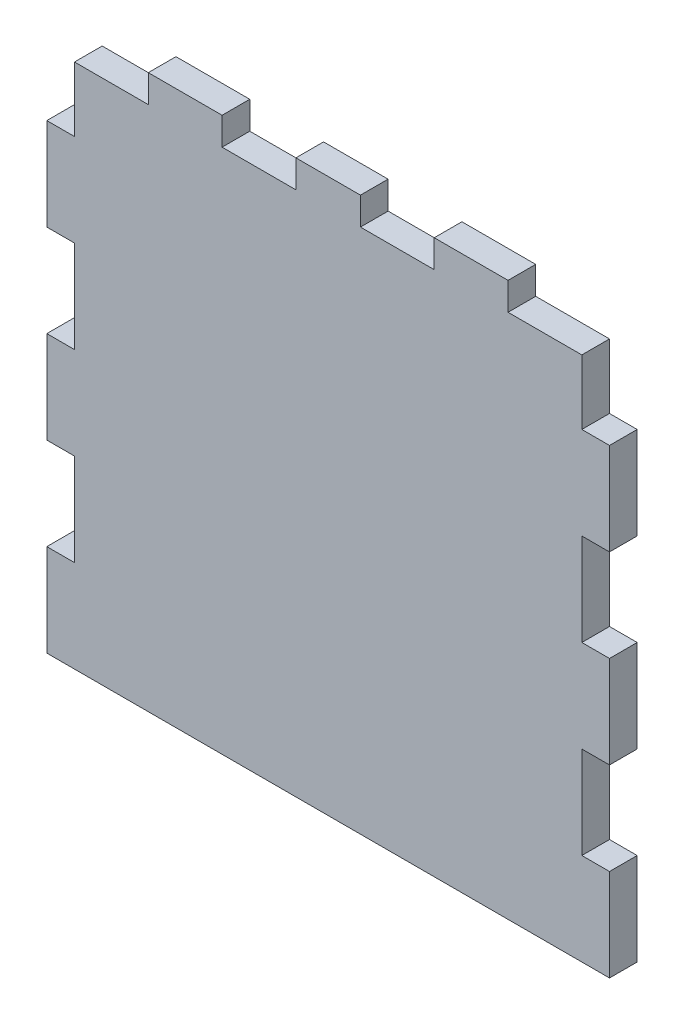
SolidWorks part; units mm, degrees
material "Beech"
ref_plane "Front Plane" through (0, 0, 0) normal (0, 0, 1) x (1, 0, 0)
ref_plane "Top Plane" through (0, 0, 0) normal (0, 1, 0) x (1, 0, 0)
ref_plane "Right Plane" through (0, 0, 0) normal (1, 0, 0) x (0, 0, -1)
sketch "Sketch1" plane through (0, 0, 0) normal (0, 0, 1) x (1, 0, 0)
  line L0 (27.5, -3) -> (-27.5, -3)
  line L1 (-27.5, -3) -> (-27.5, -60)
  line L2 (-27.5, -57) -> (27.5, -57)
  line L3 (27.5, -60) -> (27.5, -3)
  line L8 (30.5, 0) -> (-30.5, 0)
  line L9 (-30.5, 0) -> (-30.5, -60)
  line L10 (-30.5, -60) -> (30.5, -60)
  line L11 (30.5, -60) -> (30.5, 0)
  line L12 (-30.5, -20) -> (-30.5, -30)
  line L13 (-30.5, 0) -> (-27.5, 0)
  line L14 (-30.5, 0) -> (-30.5, -10)
  line L15 (-30.5, -10) -> (-27.5, -10)
  line L16 (-27.5, 0) -> (-27.5, -10)
  line L17 (-30.5, -20) -> (-27.5, -20)
  line L18 (-27.5, -20) -> (-27.5, -30)
  line L19 (-30.5, -30) -> (-27.5, -30)
  line L20 (-30.5, -40) -> (-30.5, -50)
  line L21 (-30.5, -40) -> (-27.5, -40)
  line L22 (-27.5, -40) -> (-27.5, -50)
  line L23 (-30.5, -50) -> (-27.5, -50)
  line L24 (0, 0) -> (0, -60)
  line L25 (11.5, -3) -> (3.5, -3)
  line L26 (-30.5, 0) -> (-19.5, 0)
  line L27 (-30.5, 0) -> (-30.5, -3)
  line L28 (-30.5, -3) -> (-19.5, -3)
  line L29 (-19.5, 0) -> (-19.5, -3)
  line L30 (30.5, 0) -> (19.5, 0)
  line L31 (30.5, 0) -> (30.5, -3)
  line L32 (30.5, -3) -> (19.5, -3)
  line L33 (19.5, 0) -> (19.5, -3)
  line L34 (-11.5, 0) -> (-3.5, 0)
  line L35 (-11.5, 0) -> (-11.5, -3)
  line L36 (-11.5, -3) -> (-3.5, -3)
  line L37 (-3.5, 0) -> (-3.5, -3)
  line L38 (3.5, 0) -> (3.5, -3)
  line L39 (11.5, 0) -> (3.5, 0)
  line L40 (11.5, 0) -> (11.5, -3)
  line L41 (30.5, -40) -> (27.5, -40)
  line L42 (27.5, -40) -> (27.5, -50)
  line L43 (30.5, -50) -> (27.5, -50)
  line L44 (30.5, -40) -> (30.5, -50)
  line L45 (30.5, -20) -> (27.5, -20)
  line L46 (27.5, -20) -> (27.5, -30)
  line L47 (30.5, -30) -> (27.5, -30)
  line L48 (30.5, -20) -> (30.5, -30)
  line L49 (30.5, -10) -> (27.5, -10)
  line L50 (27.5, 0) -> (27.5, -10)
  line L51 (30.5, 0) -> (27.5, 0)
  line L52 (30.5, 0) -> (30.5, -10)
  line L53 (-27.5, -3) -> (-27.5, -57) construction
  line L54 (27.5, -57) -> (27.5, -3) construction
  dimension "D3" = 10
  dimension "D5" = 11
  dimension "D6" = 11
  dimension "D7" = 8
  dimension "D8" = 8
  dimension "D2" = 3
  dimension "D4" = 3
extrude "Boss-Extrude1" add sketch "Sketch1" along normal blind 3 contours L9 L17 L1 L15 | L9 L21 L1 L19 | L23 L9 L10 L1 | L24 L0 L1 L2 | L0 L24 L2 L3 | L24 L2 L1 L10 | L2 L24 L10 L3 | L11 L43 L3 L10 | L11 L47 L3 L41 | L11 L49 L3 L45 | L8 L40 L0 L33 | L38 L8 L24 L0 | L8 L37 L0 L24 | L35 L8 L29 L0
